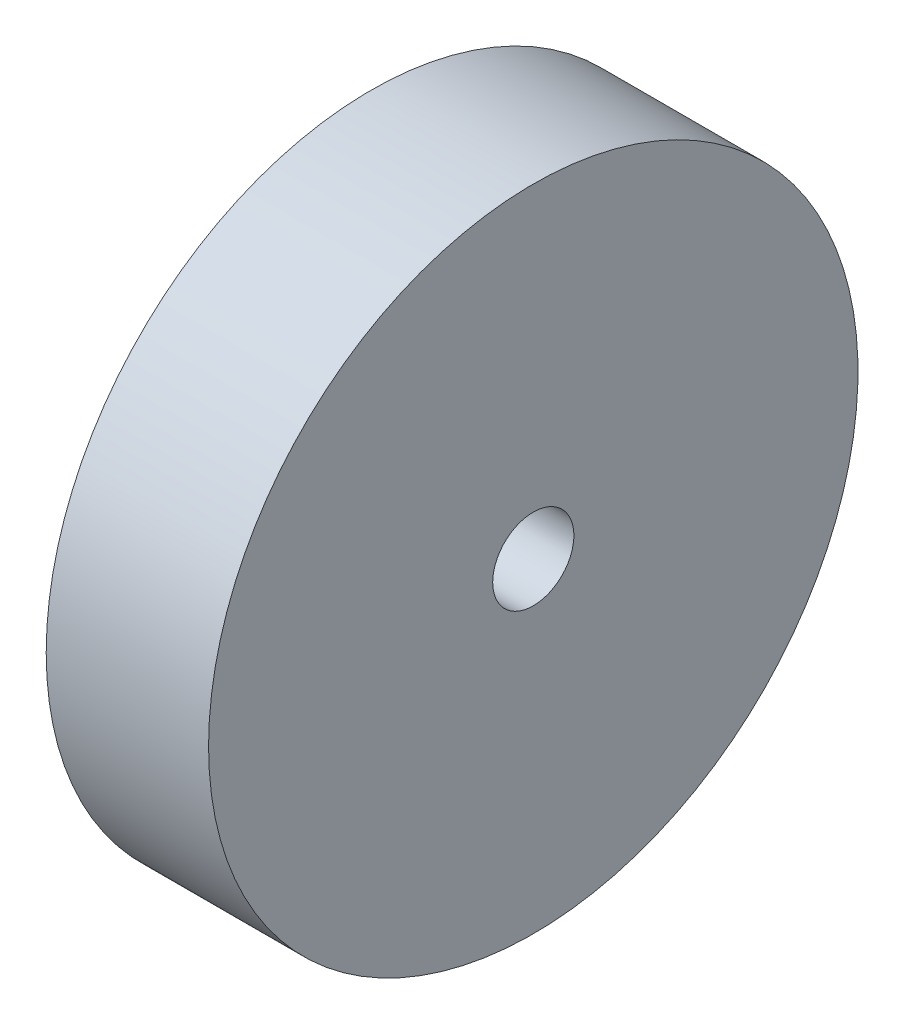
SolidWorks part; units mm, degrees
ref_plane "Front Plane" through (0, 0, 0) normal (0, 0, 1) x (1, 0, 0)
ref_plane "Top Plane" through (0, 0, 0) normal (0, 1, 0) x (1, 0, 0)
ref_plane "Right Plane" through (0, 0, 0) normal (1, 0, 0) x (0, 0, -1)
sketch "Sketch1" plane through (0, 0, 0) normal (0, 0, 1) x (1, 0, 0)
  line L0 (-6.35, 0) -> (6.35, 0) construction
  line L1 (6.35, -25.4) -> (-6.35, -25.4)
  line L2 (6.35, -25.4) -> (6.35, 25.4)
  line L3 (6.35, 25.4) -> (-6.35, 25.4)
  line L4 (-6.35, -25.4) -> (-6.35, 25.4)
  line L5 (6.35, -25.4) -> (-6.35, 25.4) construction
  line L6 (6.35, 25.4) -> (-6.35, -25.4) construction
  line L7 (-6.35, 3.175) -> (6.35, 3.175)
  point P0 (0, 0)
  dimension "D1" = 12.7
  dimension "D2" = 50.8
  dimension "D3" = 3.175
revolve "Revolve2" add sketch "Sketch1" angle 360 about L0
